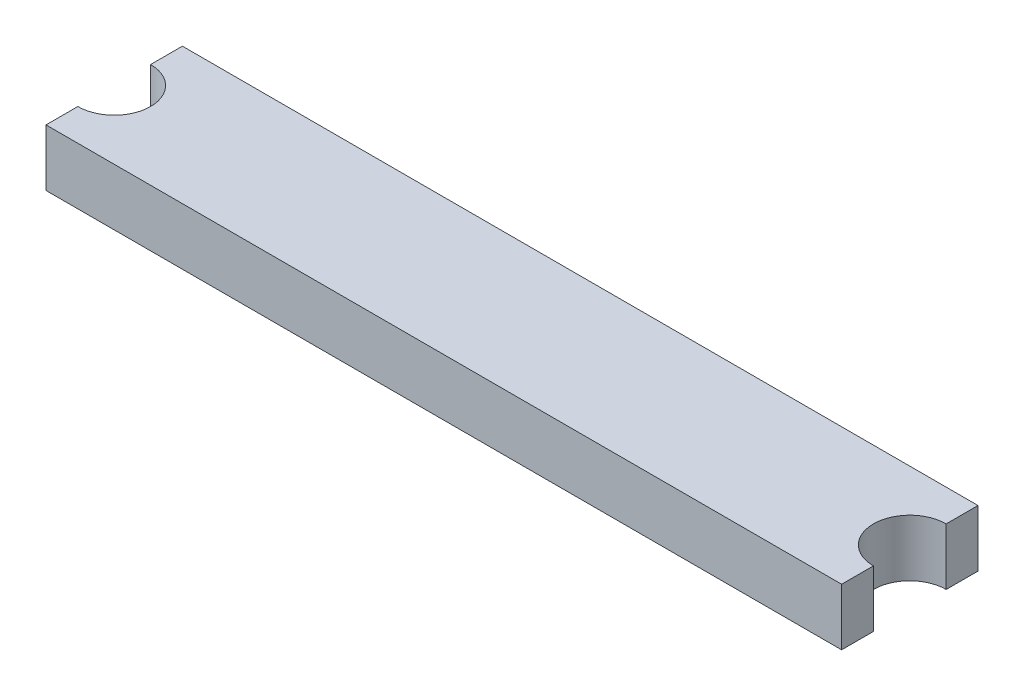
SolidWorks part; units mm, degrees
ref_plane "Front Plane" through (0, 0, 0) normal (0, 0, 1) x (1, 0, 0)
ref_plane "Top Plane" through (0, 0, 0) normal (0, 1, 0) x (1, 0, 0)
ref_plane "Right Plane" through (0, 0, 0) normal (1, 0, 0) x (0, 0, -1)
sketch "Sketch1" plane through (0, 0, 0) normal (0, 1, 0) x (1, 0, 0)
  line L1 (-175, 30) -> (175, 30)
  line L2 (-175, 30) -> (-175, -30)
  line L3 (-175, -30) -> (175, -30)
  line L4 (175, 30) -> (175, -30)
  line L5 (-175, 30) -> (175, -30) construction
  line L6 (-175, -30) -> (175, 30) construction
  point P0 (0, 0)
  dimension "D1" = 350
  dimension "D2" = 60
extrude "Boss-Extrude1" add sketch "Sketch1" along normal blind 25
sketch "Sketch2" plane through (0, 25, 0) normal (0, 1, 0) x (1, 0, 0)
  line L0 (-175, 30) -> (-175, -30) construction
  line L1 (175, -30) -> (175, 30) construction
  circle A0 centre (-175, 0) radius 16
  circle A1 centre (175, 0) radius 16
  point P8 (0, 0)
  dimension "D1" = 32
  dimension "D2" = 32
extrude "Cut-Extrude1" cut sketch "Sketch2" against normal through all contours A1 | A0
